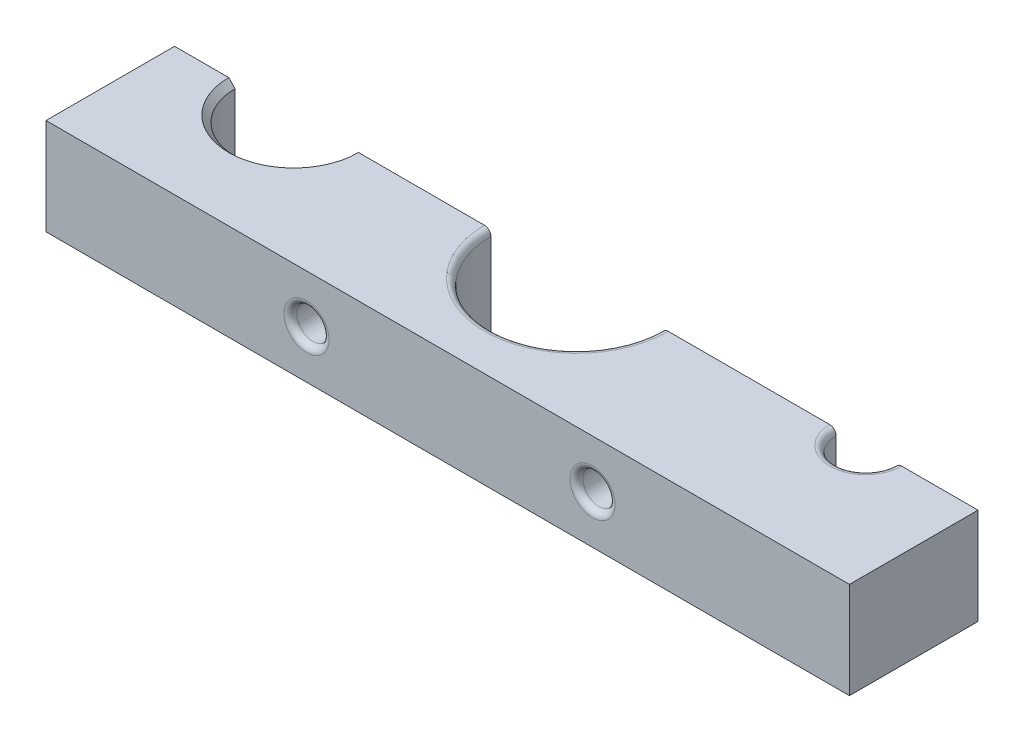
SolidWorks part; units mm, degrees
ref_plane "前基準面" through (0, 0, 0) normal (0, 0, 1) x (1, 0, 0)
ref_plane "上基準面" through (0, 0, 0) normal (0, 1, 0) x (1, 0, 0)
ref_plane "右基準面" through (0, 0, 0) normal (1, 0, 0) x (0, 0, -1)
sketch "草圖1" plane through (0, 0, 0) normal (0, 1, 0) x (1, 0, 0)
  line L1 (0, 0) -> (125, 0)
  line L2 (0, 0) -> (0, 40)
  line L3 (0, 40) -> (125, 40)
  line L4 (125, 0) -> (125, 40)
  dimension "D1" = 125
  dimension "D2" = 40
extrude "填料-伸長1" add sketch "草圖1" along normal blind 15
sketch "草圖2" plane through (0, 15, 0) normal (0, 1, 0) x (1, 0, 0)
  line L0 (-4.3311, 20) -> (135.7424, 20) construction
  line L1 (0, 0) -> (125, 0) construction
  line L2 (125, 40) -> (0, 40) construction
  line L3 (0, 40) -> (0, 0) construction
  line L4 (125, 0) -> (125, 40) construction
  circle A0 centre (18.5267, 20) radius 9.1
  circle A1 centre (107.5267, 20) radius 4.6
  circle A2 centre (62.5267, 20) radius 13.3
  point P12 (18.5267, 20)
  dimension "D1" = 26.6
  dimension "D2" = 9.2
  dimension "D3" = 18.2
  dimension "D4" = 44
  dimension "D5" = 45
  dimension "D6" = 18.5267
extrude "除料-伸長1" cut sketch "草圖2" against normal through all
sketch "草圖3" plane through (0, 0, 0) normal (0, 0, 1) x (1, 0, 0)
  line L0 (125, 7.5) -> (-7.8155, 7.5) construction
  line L1 (125, 15) -> (125, 0) construction
  line L3 (0, 15) -> (0, 0) construction
  line L5 (62.53, 26.8159) -> (62.53, -15.242) construction
  circle A0 centre (40.53, 7.5) radius 2.5
  circle A1 centre (85.03, 7.5) radius 2.5
  dimension "D1" = 5
  dimension "D2" = 5
  dimension "D3" = 40.53
  dimension "D4" = 62.53
  dimension "D5" = 22.5
chamfer "導角1" distance 1 angle 45 1 edges at (18.5267, 15, -10.9)
chamfer "導角2" distance 1 angle 45 1 edges at (18.5267, 0, -10.9)
fillet "圓角1" radius 1 4 edges at (62.5267, 0, -6.7) (107.5267, 0, -15.4) (107.5267, 15, -15.4) (62.5267, 15, -6.7)
extrude "除料-伸長2" cut sketch "草圖3" against normal through all
fillet "圓角2" radius 1 4 edges at (87.53, 7.5, -40) (43.03, 7.5, -40) (43.03, 7.5, 0) (87.53, 7.5, 0)
sketch "草圖5" plane through (0, 15, 0) normal (0, 1, 0) x (1, 0, 0)
  line L0 (0, 40) -> (0, 0) construction
  line L1 (0, 20) -> (130.4461, 20)
  line L2 (0, 20) -> (0, 51.8476)
  line L3 (0, 51.8476) -> (130.4461, 51.8476)
  line L4 (130.4461, 20) -> (130.4461, 51.8476)
extrude "除料-伸長3" cut sketch "草圖5" against normal through all
